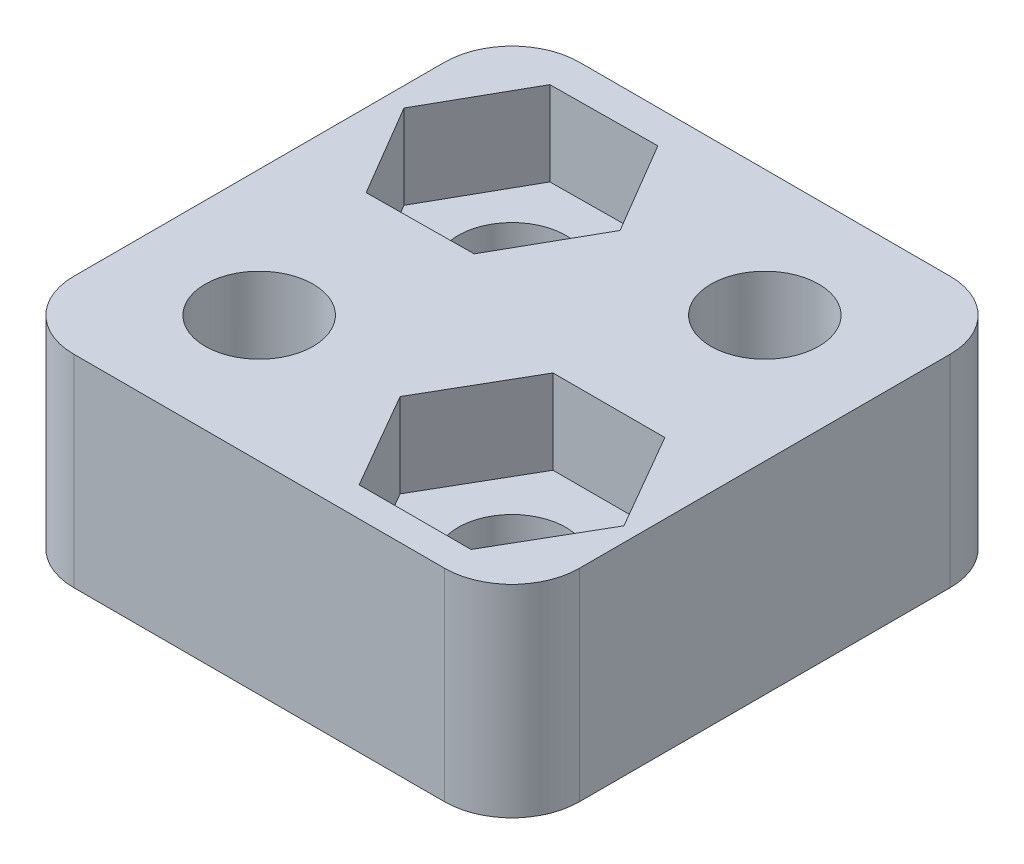
SolidWorks part; units mm, degrees
ref_plane "Front Plane" through (0, 0, 0) normal (0, 0, 1) x (1, 0, 0)
ref_plane "Top Plane" through (0, 0, 0) normal (0, 1, 0) x (1, 0, 0)
ref_plane "Right Plane" through (0, 0, 0) normal (1, 0, 0) x (0, 0, -1)
sketch "Sketch1" plane through (0, 0, 0) normal (0, 1, 0) x (1, 0, 0)
  line L0 (-7.4724, 4.8777) -> (-7.4724, -6.2987)
  line L1 (-7.4724, -6.2987) -> (7.5276, -6.2987)
  line L2 (7.5276, -6.2987) -> (7.5276, 8.7013)
  line L3 (7.5276, 8.7013) -> (-7.4724, 8.7013)
  line L4 (-7.4724, 8.7013) -> (-7.4724, 4.8777)
  circle A0 centre (-3.7224, 4.9513) radius 1.6
  circle A1 centre (3.7776, -2.5487) radius 1.6
  circle A2 centre (3.7776, 4.9513) radius 1.6
  circle A3 centre (-3.7224, -2.5487) radius 1.6
  dimension "D9" = 3.2
  dimension "D10" = 3.2
  dimension "D1" = 15
  dimension "D2" = 15
  dimension "D3" = 7.5
  dimension "D4" = 7.5
  dimension "D5" = 7.5
  dimension "D6" = 7.5
  dimension "D7" = 3.75
  dimension "D8" = 3.75
extrude "Boss-Extrude1" add sketch "Sketch1" along normal blind 6
sketch "Sketch2" plane through (0, 6, 0) normal (0, 1, 0) x (1, 0, 0)
  line L1 (-2.1093, 2.2161) -> (-0.5471, 4.9807)
  line L2 (-0.5471, 4.9807) -> (-2.1602, 7.7159)
  line L3 (-2.1602, 7.7159) -> (-5.3354, 7.6865)
  line L4 (-5.3354, 7.6865) -> (-6.8976, 4.9219)
  line L5 (-6.8976, 4.9219) -> (-5.2846, 2.1867)
  line L6 (-5.2846, 2.1867) -> (-2.1093, 2.2161)
  line L7 (7.0974, -2.5487) -> (5.4375, 0.3263)
  line L8 (5.4375, 0.3263) -> (2.1178, 0.3263)
  line L9 (2.1178, 0.3263) -> (0.4579, -2.5487)
  line L10 (0.4579, -2.5487) -> (2.1178, -5.4237)
  line L11 (2.1178, -5.4237) -> (5.4375, -5.4237)
  line L12 (5.4375, -5.4237) -> (7.0974, -2.5487)
  circle A0 centre (-3.7224, 4.9513) radius 2.75 construction
  circle A1 centre (3.7776, -2.5487) radius 2.875 construction
  dimension "D1" = 5.5
  dimension "D2" = 5.75
extrude "Cut-Extrude1" cut sketch "Sketch2" against normal blind 2.5
sketch "Sketch3" plane through (0, 0, 0) normal (0, -1, 0) x (1, 0, 0)
  circle A0 centre (3.7776, -4.9513) radius 2.75
  circle A1 centre (-3.7224, 2.5487) radius 2.75
  circle A2 centre (3.7776, -4.9513) radius 1.6 construction
  circle A3 centre (-3.7224, 2.5487) radius 1.6 construction
  dimension "D1" = 5.5
extrude "Cut-Extrude2" cut sketch "Sketch3" against normal blind 3
fillet "Fillet1" radius 2 4 edges at (-7.4724, 3, 6.2987) (7.5276, 3, 6.2987) (7.5276, 3, -8.7013) (-7.4724, 3, -8.7013)
